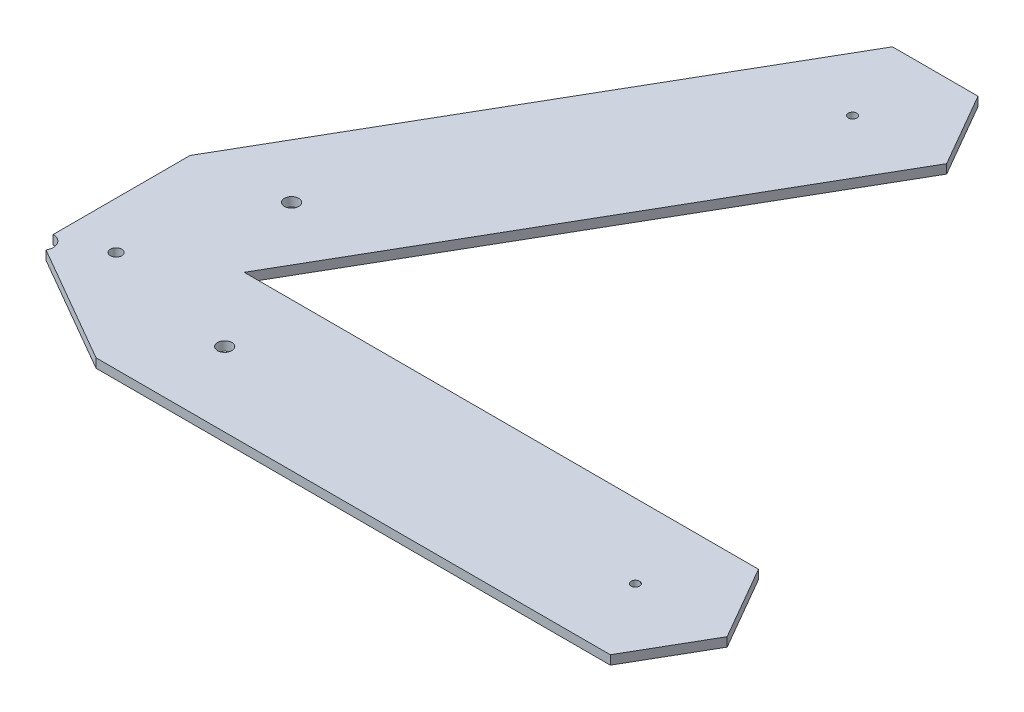
SolidWorks part; units mm, degrees
ref_plane "Front Plane" through (0, 0, 0) normal (0, 0, 1) x (1, 0, 0)
ref_plane "Top Plane" through (0, 0, 0) normal (0, 1, 0) x (1, 0, 0)
ref_plane "Right Plane" through (0, 0, 0) normal (1, 0, 0) x (0, 0, -1)
sketch "Sketch1" plane through (0, 0, 0) normal (0, 1, 0) x (1, 0, 0)
  line L0 (0, 0) -> (240.3881, 0)
  line L1 (240.3881, 0) -> (225.3881, 25.9808)
  line L2 (240.3881, 0) -> (225.3881, -25.9808)
  line L3 (0, 0) -> (120.1941, -208.1822)
  line L4 (120.1941, -208.1822) -> (135.1941, -182.2015)
  line L5 (120.1941, -208.1822) -> (90.1941, -208.1822)
  line L6 (0, 0) -> (-120.1941, -208.1822)
  line L7 (-120.1941, -208.1822) -> (-90.1941, -208.1822)
  line L8 (-120.1941, -208.1822) -> (-135.1941, -182.2015)
  line L9 (0, 0) -> (-240.3881, 0)
  line L10 (-240.3881, 0) -> (-225.3881, -25.9808)
  line L11 (-240.3881, 0) -> (-225.3881, 25.9808)
  line L12 (0, 0) -> (-120.1941, 208.1822)
  line L13 (-120.1941, 208.1822) -> (-135.1941, 182.2015)
  line L14 (-120.1941, 208.1822) -> (-90.1941, 208.1822)
  line L15 (0, 0) -> (120.1941, 208.1822)
  line L16 (120.1941, 208.1822) -> (90.1941, 208.1822)
  line L17 (120.1941, 208.1822) -> (135.1941, 182.2015)
  line L18 (135.1941, 182.2015) -> (45, 25.9808)
  line L19 (45, 25.9808) -> (225.3881, 25.9808)
  line L20 (45, -25.9808) -> (135.1941, -182.2015)
  line L21 (225.3881, -25.9808) -> (45, -25.9808)
  line L22 (0, -51.9615) -> (-90.1941, -208.1822)
  line L23 (90.1941, -208.1822) -> (0, -51.9615)
  line L24 (-45, -25.9808) -> (-225.3881, -25.9808)
  line L25 (-135.1941, -182.2015) -> (-45, -25.9808)
  line L26 (-45, 25.9808) -> (-135.1941, 182.2015)
  line L27 (-225.3881, 25.9808) -> (-45, 25.9808)
  line L28 (0, 51.9615) -> (90.1941, 208.1822)
  line L29 (-90.1941, 208.1822) -> (0, 51.9615)
  line L30 (0, 0) -> (16.4978, 9.525)
  line L31 (0, 0) -> (32.0669, 55.5414)
  line L32 (0, 0) -> (45, 25.9808)
  circle A0 centre (208.1822, 0) radius 1.5
  circle A1 centre (104.0911, -180.2911) radius 1.5
  circle A2 centre (-104.0911, -180.2911) radius 1.5
  circle A3 centre (-208.1822, 0) radius 1.5
  circle A4 centre (-104.0911, 180.2911) radius 1.5
  circle A5 centre (104.0911, 180.2911) radius 1.5
  circle A6 centre (16.4978, 9.525) radius 2
  circle A7 centre (0, -19.05) radius 2
  circle A8 centre (-16.4978, 9.525) radius 2
  circle A9 centre (32.0669, 55.5414) radius 2.5
  circle A10 centre (64.1337, 0) radius 2.5
  circle A11 centre (32.0669, -55.5414) radius 2.5
  circle A12 centre (-32.0669, -55.5414) radius 2.5
  circle A13 centre (-64.1337, 0) radius 2.5
  circle A14 centre (-32.0669, 55.5414) radius 2.5
  circle A15 centre (0, 0) radius 3.9688
  point P34 (0, 0)
  point P46 (0, 0)
  point P52 (0, 0)
  point P61 (0, 0)
  dimension "D5" = 3
  dimension "D10" = 4
  dimension "D13" = 5
  dimension "D16" = 7.9375
  dimension "D1" = 120
  dimension "D2" = 240.3881
  dimension "D3" = 30
  dimension "D4" = 32.2059
  dimension "D8" = 30
  dimension "D9" = 19.05
  dimension "D12" = 0
  dimension "D14" = 64.1337
  dimension "D6" = 6
  dimension "D7" = 6
  dimension "D11" = 3
  dimension "D15" = 6
extrude "Boss-Extrude1" add sketch "Sketch1" along normal blind 3.175 contours A15 L31 A9 L15 A5 L16 L28 L29 L14 L12 A4 A14 | A15 L32 A6 L18 L17 L15 A5 A9 L31 | A15 L0 A10 A0 L1 L19 L32 A6 | A15 L3 A11 A1 L4 L20 L21 L2 L0 A0 A10 | A15 L6 A12 A2 L7 L22 L23 L5 L3 A1 A11 A7 | A15 L9 A13 A3 L10 L24 L25 L8 L6 A2 A12 | A15 L12 A14 A4 L13 L26 L27 L11 L9 A3 A13 A8
sketch "Sketch2" plane through (0, 3.175, 0) normal (0, 1, 0) x (1, 0, 0)
  line L0 (0, 0) -> (0, 51.9615)
  line L1 (0, 0) -> (45, -25.9808)
  line L2 (0, 51.9615) -> (0, 264.0515)
  line L3 (45, -25.9808) -> (228.6753, -132.0258)
  arc A0 (228.6753, -132.0258) -> (0, 264.0515) centre (0, 0) cw
  line M4 (90.1941, -208.1822) -> (120.1941, -208.1822)
  line M5 (120.1941, -208.1822) -> (135.1941, -182.2015)
  line M6 (135.1941, -182.2015) -> (45, -25.9808)
  line M15 (0, 51.9615) -> (-90.1941, 208.1822)
  line M16 (-90.1941, 208.1822) -> (-120.1941, 208.1822)
  line M17 (-120.1941, 208.1822) -> (-135.1941, 182.2015)
  line M18 (-135.1941, 182.2015) -> (-45, 25.9808)
  line M19 (-45, 25.9808) -> (-225.3881, 25.9808)
  line M20 (-225.3881, 25.9808) -> (-240.3881, 0)
  line M21 (-240.3881, 0) -> (-225.3881, -25.9808)
  line M22 (-225.3881, -25.9808) -> (-45, -25.9808)
  line M23 (-45, -25.9808) -> (-135.1941, -182.2015)
  line M24 (-135.1941, -182.2015) -> (-120.1941, -208.1822)
  line M25 (-120.1941, -208.1822) -> (-90.1941, -208.1822)
  line M26 (-90.1941, -208.1822) -> (0, -51.9615)
  line M27 (0, -51.9615) -> (90.1941, -208.1822)
  circle M28 centre (104.0911, -180.2911) radius 1.5
  circle M29 centre (32.0669, -55.5414) radius 2.5
  circle M32 centre (0, 0) radius 3.9688
  circle M33 centre (-104.0911, -180.2911) radius 1.5
  circle M35 centre (-32.0669, -55.5414) radius 2.5
  circle M36 centre (-208.1822, 0) radius 1.5
  circle M39 centre (-64.1337, 0) radius 2.5
  circle M40 centre (-104.0911, 180.2911) radius 1.5
  circle M41 centre (-32.0669, 55.5414) radius 2.5
  circle M42 centre (-16.4978, 9.525) radius 2
  circle M43 centre (0, -19.05) radius 2
  dimension "D1" = 212.09
  dimension "D2" = 212.09
extrude "Cut-Extrude1" cut sketch "Sketch2" against normal blind 3.175 contours A0 L3 L2 M6 M5 M4 M27 M26 M25 M24 M23 M22 M21 M20 M19 M18 M17 M16 M15 | L1 L0 M32 M15 M16 M17 M18 M19 M20 M21 M22 M23 M24 M25 M26 M27 M4 M5 M6 M28 M36 M40 M42 M43 M41 M39 M35 M33 M29
